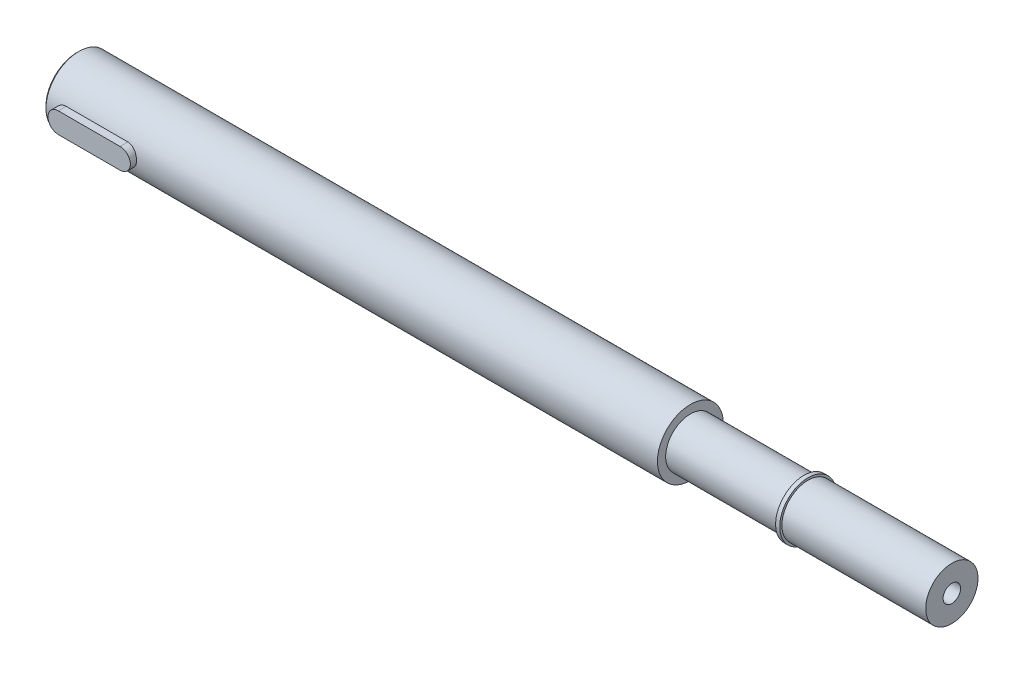
SolidWorks part; units mm, degrees
ref_plane "Front Plane" through (0, 0, 0) normal (0, 0, 1) x (1, 0, 0)
ref_plane "Top Plane" through (0, 0, 0) normal (0, 1, 0) x (1, 0, 0)
ref_plane "Right Plane" through (0, 0, 0) normal (1, 0, 0) x (0, 0, -1)
sketch "Sketch1" plane through (0, 0, 0) normal (0, 0, 1) x (1, 0, 0)
  line L0 (0, 0) -> (-117.8294, 0)
  line L1 (-117.8294, 0) -> (-117.8294, 15)
  line L2 (-116.8294, 16) -> (180.1706, 16)
  line L3 (180.1706, 16) -> (180.1706, 12)
  line L4 (180.1706, 12) -> (235.3206, 12)
  line L5 (307.1706, 11) -> (307.1706, 0)
  line L6 (307.1706, 0) -> (0, 0)
  line L7 (-117.8294, 15) -> (-116.8294, 16)
  line L10 (237.3206, 12.7) -> (307.1706, 12.7)
  line L11 (307.1706, 12.7) -> (307.1706, 11)
  line L12 (237.3206, 12.7) -> (237.3206, 13.7577)
  line L13 (237.3206, 13.7577) -> (235.3206, 13.7577)
  line L14 (235.3206, 13.7577) -> (235.3206, 12)
  point P4 (-117.8294, 16)
  point P7 (307.1706, 12)
  dimension "D1" = 16
  dimension "D2" = 12
  dimension "D3" = 298
  dimension "D4" = 425
  dimension "D5" = 12.7
  dimension "D6" = 69.85
  dimension "D9" = 2
revolve "Revolve1" add sketch "Sketch1" angle 360 about L0
ref_plane "Plane1" through (0, 0, 19) normal (0, 0, 1) x (1, 0, 0)
sketch "Sketch2" plane through (0, 0, 19) normal (0, 0, 1) x (1, 0, 0)
  line L0 (-107.8294, 0) -> (-77.8294, 0) construction
  line L1 (-107.8294, 5) -> (-77.8294, 5)
  line L2 (-107.8294, -5) -> (-77.8294, -5)
  line L3 (-117.8294, 15) -> (-117.8294, -15) construction
  arc A0 (-107.8294, 5) -> (-107.8294, -5) centre (-107.8294, 0) ccw
  arc A1 (-77.8294, -5) -> (-77.8294, 5) centre (-77.8294, 0) ccw
  point P3 (-92.8294, 0)
  dimension "D1" = 5
  dimension "D2" = 10
  dimension "D3" = 40
extrude "Boss-Extrude1" add sketch "Sketch2" against normal blind 10
hole_wizard "M10x1.5 Tapped Hole1" positions "Sketch3" profile "Sketch4" tap size "M10x1.5" standard "ANSI Metric"
sketch "Sketch3" plane through (307.1706, 0, 0) normal (1, 0, 0) x (0, 0, -1)
  point P0 (0, 0)
sketch "Sketch4" plane through (307.1706, 0, 0) normal (0, 1, 0) x (0, 0, -1)
  line L0 (0, 0) -> (0, 27.0537)
  line L1 (0, 27.0537) -> (4.25, 24.5)
  line L2 (4.25, 24.5) -> (4.25, 0)
  line L5 (4.25, 0) -> (0, 0)
  line L10 (0, 27.0537) -> (-4.25, 24.5) construction
  line L11 (0, -6.35) -> (0, 107.95) construction
  dimension "Tap Drill Dia." = 8.5
  dimension "Tap Drill Depth" = 24.5
  dimension "Drill Angle" = 118
cosmetic thread "Hole Thread1" parameters "D1"=20, "D2"=10
